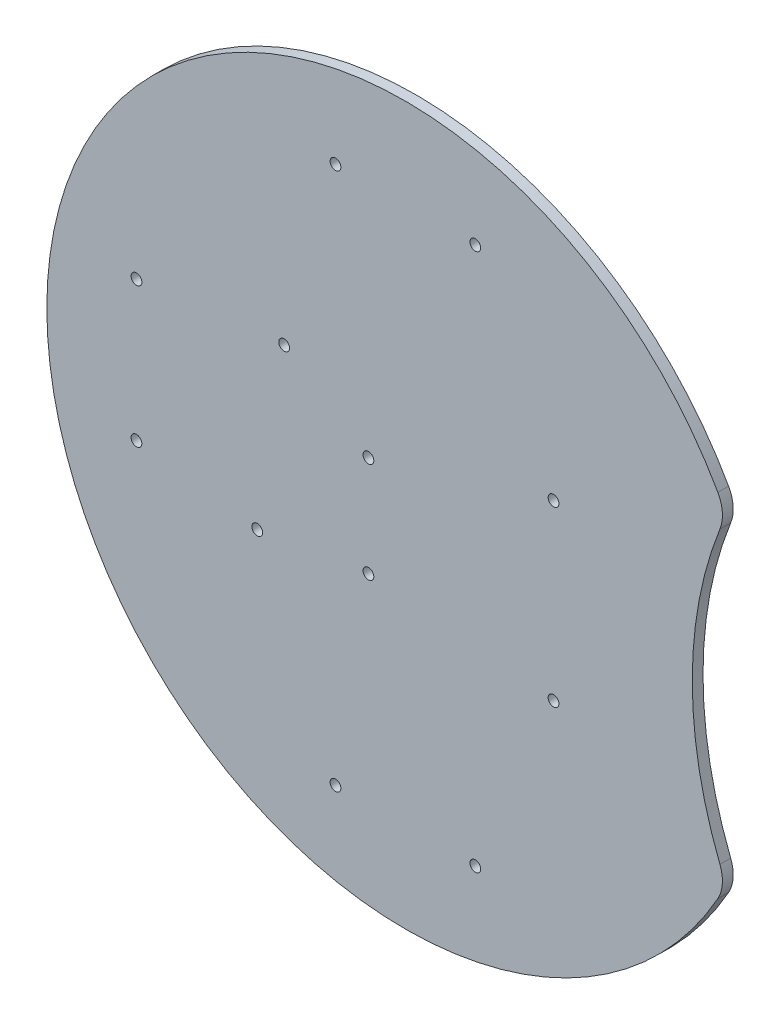
SolidWorks part; units mm, degrees
ref_plane "Alzado" through (0, 0, 0) normal (0, 0, 1) x (1, 0, 0)
ref_plane "Planta" through (0, 0, 0) normal (0, 1, 0) x (1, 0, 0)
ref_plane "Vista lateral" through (0, 0, 0) normal (1, 0, 0) x (0, 0, -1)
sketch "Croquis1" plane through (0, 0, 0) normal (0, 0, 1) x (1, 0, 0)
  circle A0 centre (0, 0) radius 100
  dimension "D1" = 200
extrude "Saliente-Extruir1" add sketch "Croquis1" along normal blind 3
sketch "Croquis3" plane through (0, 0, 3) normal (0, 0, 1) x (1, 0, 0)
  line L0 (0, 0) -> (190, 0) construction
  circle A0 centre (190, 0) radius 110
  dimension "D1" = 220
  dimension "D2" = 190
extrude "Cortar-Extruir1" cut sketch "Croquis3" against normal blind 3
fillet "Redondeo1" radius 10 2 edges at (89.4737, -44.6594, 1.5) (89.4737, 44.6594, 1.5)
sketch "Croquis4" plane through (0, 0, 3) normal (0, 0, 1) x (1, 0, 0)
  line L0 (41.315, 0) -> (-41.315, 0) construction
  line L1 (41.315, 0) -> (80, 0) construction
  line L2 (41.315, 24.17) -> (41.315, -24.17) construction
  line L3 (41.315, 24.17) -> (80, 0) construction
  line L4 (41.315, -24.17) -> (-41.315, -24.17) construction
  line L5 (-33.815, 24.17) -> (-10.3112, 8.7146) construction
  line L6 (41.315, 24.17) -> (-33.815, 24.17) construction
  line L7 (-10.3112, 8.7146) -> (41.315, 24.17) construction
  line L8 (-41.315, -24.17) -> (-10.3156, -19.2975) construction
  line L9 (-10.3156, -19.2975) -> (41.315, -24.17) construction
  circle A0 centre (-33.815, 24.17) radius 1.5
  arc A1 (87.7193, 40.4803) -> (87.7193, -40.4803) centre (190, 0) ccw construction
  circle A2 centre (-41.315, -24.17) radius 1.5
  circle A3 centre (41.315, -24.17) radius 1.5
  circle A4 centre (41.315, 24.17) radius 1.5
  circle A5 centre (-10.3156, -19.2975) radius 1.5
  circle A6 centre (-10.3112, 8.7146) radius 1.5
  dimension "D2" = 75.13
  dimension "D3" = 82.63
  dimension "D4" = 31.38
  dimension "D5" = 51.86
  dimension "D9" = 3
  dimension "D13" = 3
  dimension "D14" = 150.6367
  dimension "D15" = 150.6367
  dimension "D8" = 3
  dimension "D10" = 3
  dimension "D11" = 3
  dimension "D12" = 3
  dimension "D1" = 38.685
  dimension "D6" = 28.13
  dimension "D7" = 53.89
extrude "Cortar-Extruir2" cut sketch "Croquis4" against normal through all
sketch "Croquis5" plane through (0, 0, 3) normal (0, 0, 1) x (1, 0, 0)
  line L0 (-100, 0) -> (-75, 0) construction
  line L1 (-75, 19.5) -> (-75, -19.5) construction
  arc A0 (87.1345, 49.0671) -> (87.1345, -49.0671) centre (0, 0) ccw construction
  circle A1 centre (-75, 19.5) radius 1.5
  circle A2 centre (-75, -19.5) radius 1.5
  circle A3 centre (19.5, 75) radius 1.5
  circle A4 centre (-19.5, 75) radius 1.5
  circle A7 centre (-19.5, -75) radius 1.5
  circle A8 centre (19.5, -75) radius 1.5
  circle A9 centre (75, 19.5) radius 1.5 [skipped]
  circle A10 centre (75, -19.5) radius 1.5 [skipped]
  point P26 (0, 0)
  dimension "D1" = 3
  dimension "D2" = 3
  dimension "D3" = 39
  dimension "D6" = 4
extrude "Cortar-Extruir3" cut sketch "Croquis5" against normal through all
